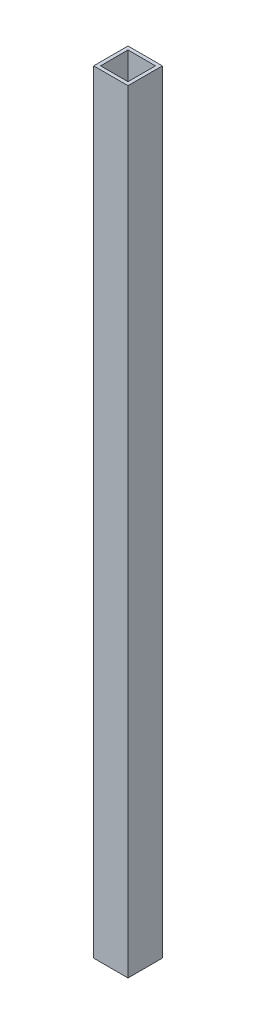
SolidWorks part; units mm, degrees
material "Aleación 1060"
ref_plane "Alzado" through (0, 0, 0) normal (0, 0, 1) x (1, 0, 0)
ref_plane "Planta" through (0, 0, 0) normal (0, 1, 0) x (1, 0, 0)
ref_plane "Vista lateral" through (0, 0, 0) normal (1, 0, 0) x (0, 0, -1)
sketch "Croquis1" plane through (0, 0, 0) normal (0, 1, 0) x (1, 0, 0)
  line L0 (-8, -8) -> (-8, 8)
  line L1 (-10, -10) -> (10, -10)
  line L2 (-10, -10) -> (-10, 10)
  line L3 (-10, 10) -> (10, 10)
  line L4 (10, -10) -> (10, 10)
  line L5 (-10, -10) -> (10, 10) construction
  line L6 (-10, 10) -> (10, -10) construction
  line L7 (-8, 8) -> (8, 8)
  line L8 (8, -8) -> (8, 8)
  line L9 (-8, -8) -> (8, -8)
  point P0 (0, 0)
  dimension "D1" = 20
  dimension "D2" = 20
  dimension "D3" = 2
extrude "Saliente-Extruir1" add sketch "Croquis1" along normal mid plane 450
